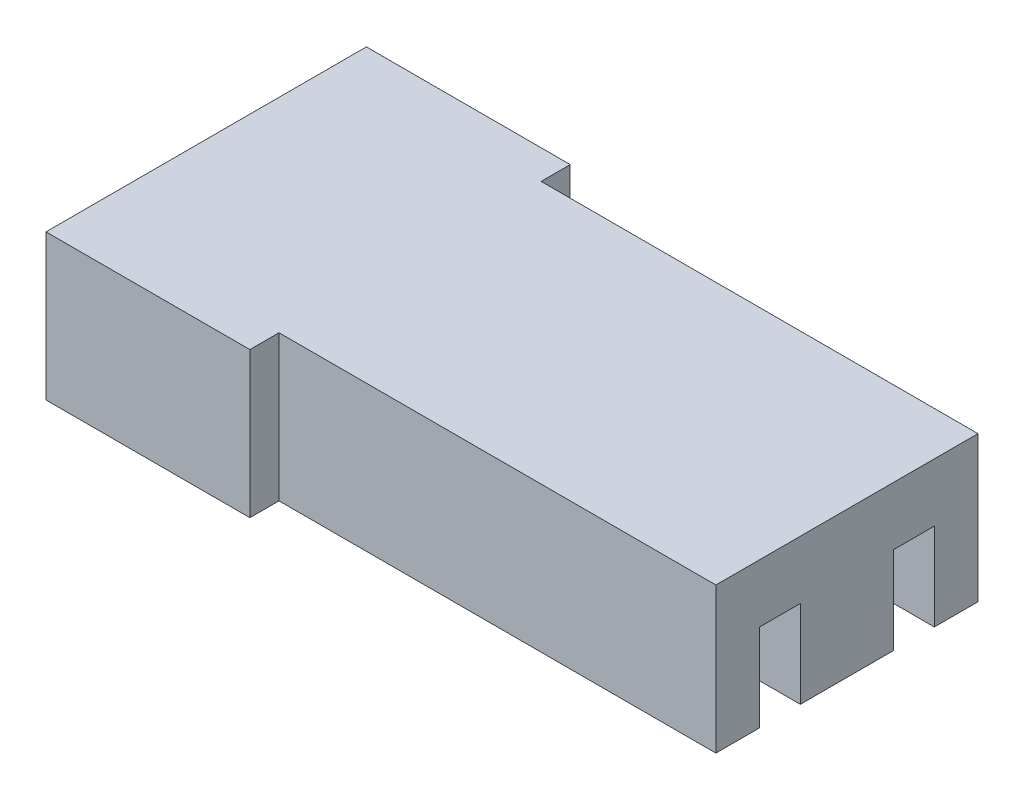
SolidWorks part; units mm, degrees
ref_plane "Front Plane" through (0, 0, 0) normal (0, 0, 1) x (1, 0, 0)
ref_plane "Top Plane" through (0, 0, 0) normal (0, 1, 0) x (1, 0, 0)
ref_plane "Right Plane" through (0, 0, 0) normal (1, 0, 0) x (0, 0, -1)
sketch "Sketch1" plane through (0, 0, 0) normal (0, 1, 0) x (1, 0, 0)
  line L1 (-7.5, -4.5) -> (7.5, -4.5)
  line L3 (-7.5, 4.5) -> (7.5, 4.5)
  line L5 (-7.5, -4.5) -> (7.5, 4.5) construction
  line L6 (-7.5, 4.5) -> (7.5, -4.5) construction
  line L10 (-7.5, 4.5) -> (-7.5, 5.5)
  line L11 (-7.5, 5.5) -> (-14.5, 5.5)
  line L12 (-14.5, 5.5) -> (-14.5, -5.5)
  line L13 (-14.5, -5.5) -> (-7.5, -5.5)
  line L14 (-7.5, -5.5) -> (-7.5, -4.5)
  line L15 (7.5, 4.5) -> (7.5, -4.5)
  point P0 (0, 0)
  dimension "D1" = 9
  dimension "D2" = 15
  dimension "D6" = 1
  dimension "D7" = 7
extrude "Boss-Extrude1" add sketch "Sketch1" along normal blind 2
sketch "Sketch2" plane through (0, 0, 0) normal (0, 1, 0) x (1, 0, 0)
  line L0 (7.5, 4.5) -> (-7.5, 4.5)
  line L1 (-7.5, 4.5) -> (-7.5, 5.5)
  line L2 (-7.5, 5.5) -> (-14.5, 5.5)
  line L3 (-14.5, 5.5) -> (-14.5, 3.5)
  line L4 (-14.5, 5.5) -> (-14.5, -5.5) construction
  line L5 (-14.5, 3.5) -> (0.5, 3.5)
  line L6 (0.5, 3.5) -> (0.5, 3)
  line L7 (0.5, 3) -> (7.5, 3)
  line L8 (7.5, -4.5) -> (7.5, 4.5) construction
  line L9 (7.5, 3) -> (7.5, 4.5)
  line L11 (7.5, -4.5) -> (-7.5, -4.5)
  line L12 (-7.5, -4.5) -> (-7.5, -5.5)
  line L13 (-7.5, -5.5) -> (-14.5, -5.5)
  line L14 (-14.5, -5.5) -> (-14.5, -3.5)
  line L15 (-14.5, -3.5) -> (0.5, -3.5)
  line L16 (0.5, -3.5) -> (0.5, -3)
  line L17 (0.5, -3) -> (7.5, -3)
  line L18 (7.5, -3) -> (7.5, -4.5)
  line L20 (0.5, 1.6) -> (7.5, 1.6)
  line L21 (7.5, 1.6) -> (7.5, -1.6)
  line L22 (7.5, -1.6) -> (0.5, -1.6)
  line L23 (0.5, -1.6) -> (0.5, 1.6)
  dimension "D1" = 1.5
  dimension "D2" = 7
  dimension "D3" = 1.4
  dimension "D4" = 1.4
  dimension "D5" = 2
extrude "Boss-Extrude2" add sketch "Sketch2" against normal blind 3
sketch "Sketch3" plane through (0, -3, 0) normal (0, -1, 0) x (1, 0, 0)
  line L0 (-14.5, 5.5) -> (-14.5, 2.3911)
  line L1 (-14.5, -3.5) -> (-14.5, 3.5) construction
  line L2 (-7.5, 5.5) -> (-14.5, 5.5)
  line L3 (-7.5, 5.5) -> (-7.5, 2.3911)
  line L4 (-7.5, 2.3911) -> (-14.5, 2.3911)
  line L5 (-7.5, -5.5) -> (-14.5, -5.5)
  line L6 (-14.5, -5.5) -> (-14.5, -2.3911)
  line L7 (-7.5, -5.5) -> (-7.5, -2.3911)
  line L8 (-7.5, -2.3911) -> (-14.5, -2.3911)
  dimension "D1" = 3.1089
extrude "Boss-Extrude3" add sketch "Sketch3" against normal blind 2
